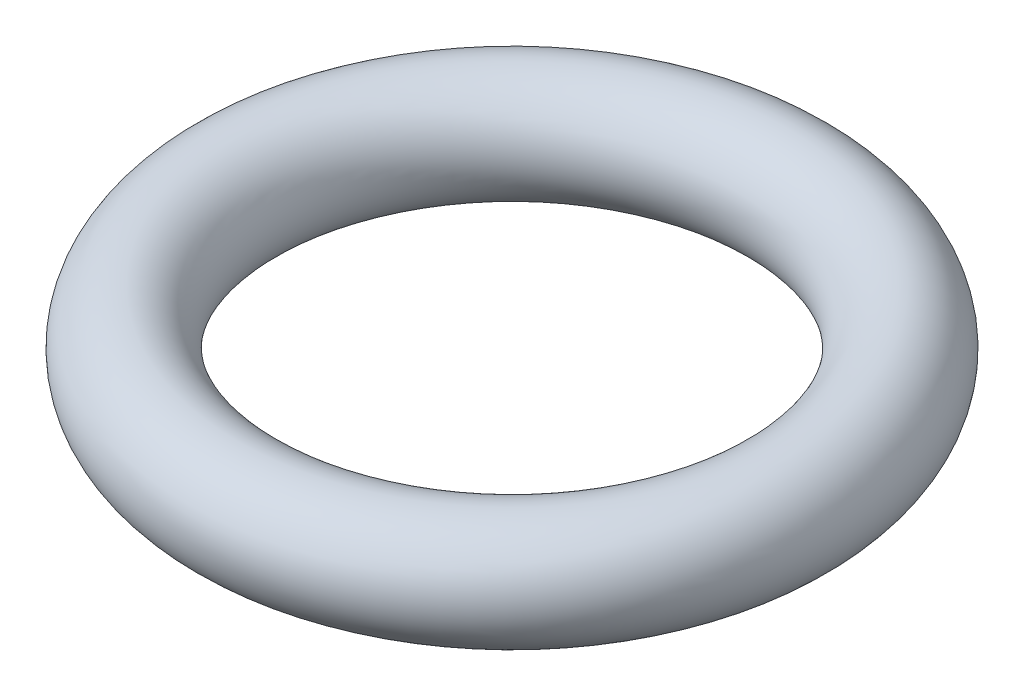
SolidWorks part; units mm, degrees
material "Rubber"
ref_plane "Front Plane" through (0, 0, 0) normal (0, 0, 1) x (1, 0, 0)
ref_plane "Top Plane" through (0, 0, 0) normal (0, 1, 0) x (1, 0, 0)
ref_plane "Right Plane" through (0, 0, 0) normal (1, 0, 0) x (0, 0, -1)
sketch "Sketch1" plane through (0, 0, 0) normal (0, 0, 1) x (1, 0, 0)
  line L0 (0, 0) -> (0, 13.3958) construction
  circle A0 centre (5, 0) radius 1
  dimension "D1" = 2
  dimension "D2" = 5
revolve "Revolve1" add sketch "Sketch1" angle 360 about L0
